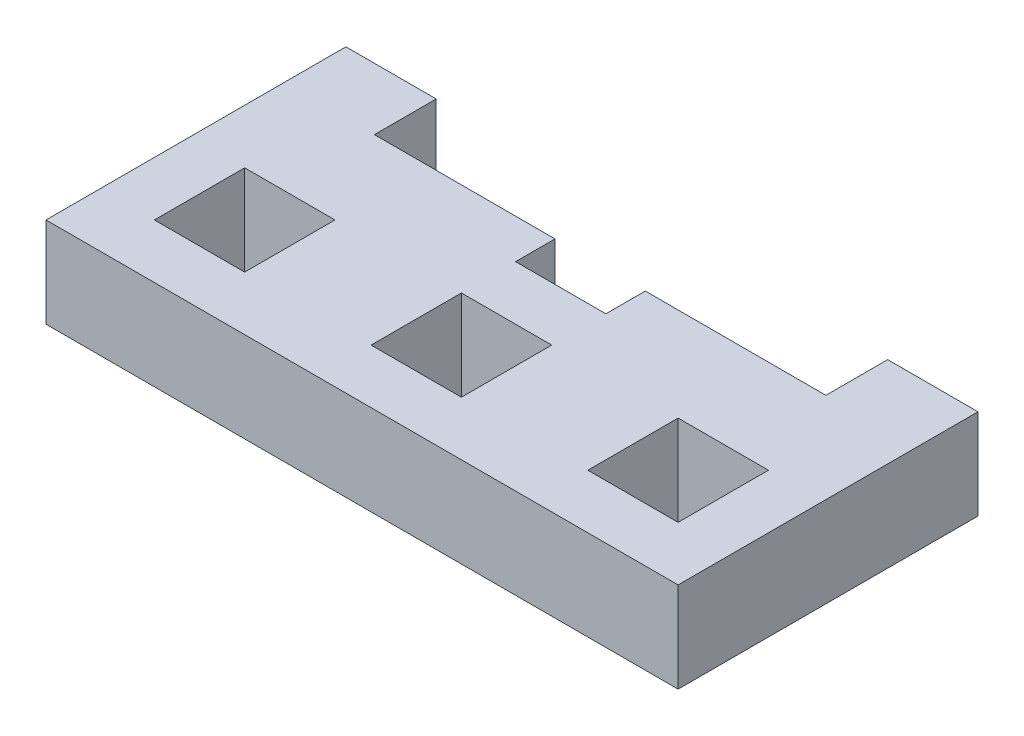
SolidWorks part; units mm, degrees
ref_plane "Front Plane" through (0, 0, 0) normal (0, 0, 1) x (1, 0, 0)
ref_plane "Top Plane" through (0, 0, 0) normal (0, 1, 0) x (1, 0, 0)
ref_plane "Right Plane" through (0, 0, 0) normal (1, 0, 0) x (0, 0, -1)
sketch "Sketch1" plane through (0, 0, 0) normal (0, 1, 0) x (1, 0, 0)
  line L0 (-22.225, 0) -> (22.225, 0) construction
  line L1 (-22.225, -6.985) -> (22.225, -6.985)
  line L2 (-22.225, -6.985) -> (-22.225, 9.7575)
  line L3 (-15.875, 9.7575) -> (-3.175, 9.7575)
  line L4 (22.225, -6.985) -> (22.225, 9.7575)
  line L5 (0, 6.985) -> (0, -6.985) construction
  line L6 (-3.175, 9.7575) -> (-3.175, 6.985)
  line L7 (-3.175, 6.985) -> (3.175, 6.985)
  line L8 (3.175, 6.985) -> (3.175, 9.7575)
  line L9 (3.175, 9.7575) -> (15.875, 9.7575)
  line L10 (-18.415, 3.175) -> (-12.065, -3.175) construction
  line L11 (-3.175, 3.175) -> (3.175, 3.175)
  line L12 (-3.175, 3.175) -> (-3.175, -3.175)
  line L13 (-3.175, -3.175) -> (3.175, -3.175)
  line L15 (22.225, 9.7575) -> (22.225, 14.1025)
  line L16 (3.175, 3.175) -> (3.175, -3.175)
  line L17 (-3.175, 3.175) -> (3.175, -3.175) construction
  line L18 (-3.175, -3.175) -> (3.175, 3.175) construction
  line L19 (-12.065, 3.175) -> (-18.415, -3.175) construction
  line L20 (12.065, 3.175) -> (18.415, -3.175) construction
  line L21 (12.065, -3.175) -> (18.415, 3.175) construction
  line L22 (18.415, -3.175) -> (12.065, -3.175)
  line L23 (18.415, -3.175) -> (18.415, 3.175)
  line L24 (18.415, 3.175) -> (12.065, 3.175)
  line L25 (12.065, -3.175) -> (12.065, 3.175)
  line L26 (22.225, 14.1025) -> (15.875, 14.1025)
  line L27 (15.875, 14.1025) -> (15.875, 9.7575)
  line L28 (-15.875, 14.1025) -> (-15.875, 9.7575)
  line L29 (-22.225, 14.1025) -> (-15.875, 14.1025)
  line L30 (-12.065, -3.175) -> (-12.065, 3.175)
  line L31 (-18.415, 3.175) -> (-12.065, 3.175)
  line L32 (-18.415, -3.175) -> (-18.415, 3.175)
  line L33 (-18.415, -3.175) -> (-12.065, -3.175)
  line L34 (-22.225, 9.7575) -> (-22.225, 14.1025)
  point P8 (0, 0)
  point P12 (0, 6.985)
  point P16 (0, 0)
  point P22 (-15.24, 0)
  point P23 (15.24, 0)
  dimension "D1" = 44.45
  dimension "D2" = 3.81
  dimension "D3" = 6.35
  dimension "D4" = 3.81
  dimension "D5" = 12.065
  dimension "D6" = 6.35
  dimension "D7" = 3.81
  dimension "D9" = 2.7725
  dimension "D10" = 4.345
  dimension "D11" = 6.35
extrude "Boss-Extrude1" add sketch "Sketch1" along normal blind 6.35
equation "\"Ball Diameter\"= 1.75in"
equation "\"Sheet Thickness\"= 0.25in"
equation "\"Screw Diameter\"= .17in"
equation "\"Robot Diameter\"= 14in"
equation "\"Castor Screw Diameter\"= 0.22in"
equation "\"Wheel Diameter\" = 4in"
equation "\"Nut Diameter\" = 8.4mm"
equation "\"Nut Height\" = 2.9mm"
equation "\"Screw Height\" = 0.55in"
equation "\"Pulley Diameter\" = 1in"
equation "\"Reactor Height\" = 14in"
equation "\"Elevator Height\" = 11.5in"
equation "\"Elevator Width\" = \"Ball Diameter\" + 0.25in"
equation "\"Elevator Bearing Diameter\" = sqr(2*(\"Sheet Thickness\"^2)) + 0.2in"
equation "\"Elevator Axle Endcap Diameter\" = \"Pulley Diameter\" + 0.25in"
equation "\"Elevator Axle Length\" = \"Elevator Width\" + 8*\"Sheet Thickness\""
equation "\"Elevator Clearance from Axis\" = (\"Pulley Diameter\"/2) + \"Ball Diameter\" + 0.5in"
equation "\"D1@Sketch1\"=\"Elevator Width\"-0.25in"
equation "\"D3@Sketch1\" = \"Sheet Thickness\""
equation "\"D6@Sketch1\"=\"Sheet Thickness\""
equation "\"D9@Sketch1\"=(0.3in - ((\"Elevator Axle Endcap Diameter\"-\"Pulley Diameter\")/2 - 1.1mm))/2"
equation "\"D10@Sketch1\"=(\"Elevator Axle Endcap Diameter\"-\"Pulley Diameter\")/2 - 1.1mm + 2.27mm"
equation "\"D1@Boss-Extrude1\"=\"Sheet Thickness\""
